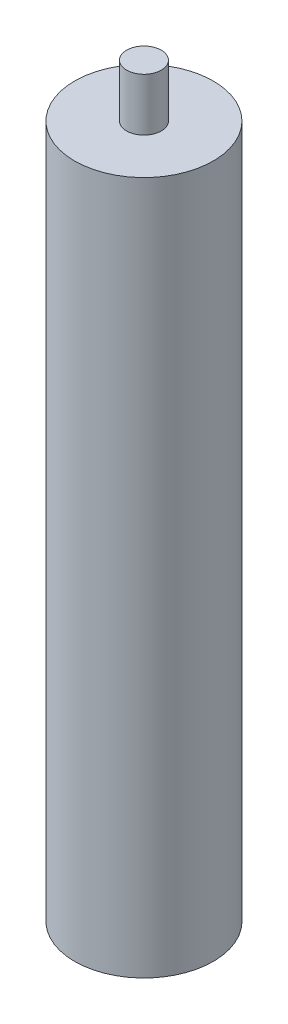
SolidWorks part; units mm, degrees
ref_plane "Front Plane" through (0, 0, 0) normal (0, 0, 1) x (1, 0, 0)
ref_plane "Top Plane" through (0, 0, 0) normal (0, 1, 0) x (1, 0, 0)
ref_plane "Right Plane" through (0, 0, 0) normal (1, 0, 0) x (0, 0, -1)
sketch "Sketch1" plane through (0, 0, 0) normal (0, 1, 0) x (1, 0, 0)
  circle A0 centre (0, 0) radius 12.7
  dimension "D1" = 25.4
extrude "Boss-Extrude1" add sketch "Sketch1" along normal blind 127
sketch "Sketch2" plane through (0, 127, 0) normal (0, 1, 0) x (1, 0, 0)
  circle A0 centre (0, 0) radius 3.175
  dimension "D1" = 6.35
extrude "Boss-Extrude2" add sketch "Sketch2" along normal blind 9.652
